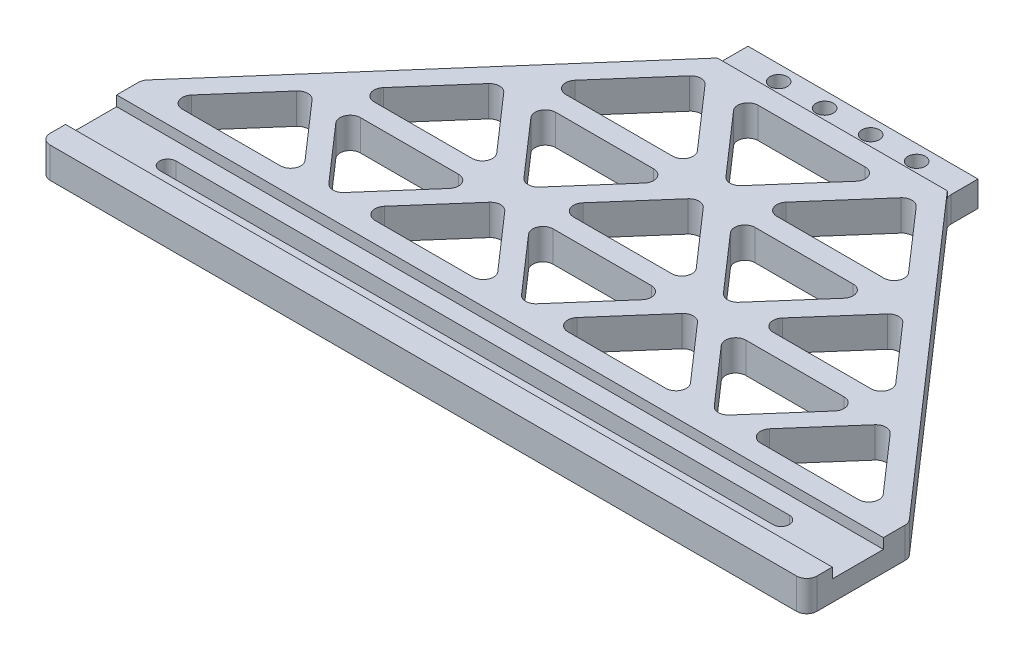
SolidWorks part; units mm, degrees
material "Сплав 2024"
ref_plane "Спереди" through (0, 0, 0) normal (0, 0, 1) x (1, 0, 0)
ref_plane "Сверху" through (0, 0, 0) normal (0, 1, 0) x (1, 0, 0)
ref_plane "Справа" through (0, 0, 0) normal (1, 0, 0) x (0, 0, -1)
sketch "Эскиз1" plane through (0, 0, 0) normal (0, 1, 0) x (1, 0, 0)
  line L0 (-22.5, 0) -> (22.5, 0) construction
  line L1 (-22.5, 3) -> (22.5, 3)
  line L2 (-22.5, 3) -> (-22.5, -3)
  line L3 (-22.5, -3) -> (22.5, -3) construction
  line L4 (22.5, 3) -> (22.5, -3)
  line L5 (-22.5, 3) -> (22.5, -3) construction
  line L6 (-22.5, -3) -> (22.5, 3) construction
  line L7 (0, 3) -> (0, -3) construction
  line L8 (-22.5, -3) -> (-75, -63)
  line L9 (-75, -63) -> (-75, -83)
  line L10 (-75, -83) -> (75, -83)
  line L11 (75, -83) -> (75, -63)
  line L12 (75, -63) -> (22.5, -3)
  line L13 (0, -3) -> (0, -163) construction
  line L14 (75, -63) -> (-75, -63) construction
  line L15 (-13.5, 3) -> (-13.5, -3) construction
  line L16 (-4.5, 3) -> (-4.5, -3) construction
  line L17 (4.5, 3) -> (4.5, -3) construction
  line L18 (13.5, 3) -> (13.5, -3) construction
  point P0 (0, 0)
  point P10 (0, -83)
  dimension "D1" = 45
  dimension "D2" = 6
  dimension "D3" = 150
  dimension "D4" = 80
  dimension "D5" = 20
  dimension "D6" = 9
  dimension "D7" = 9
  dimension "D8" = 9
  dimension "D9" = 9
extrude "Бобышка-Вытянуть1" add sketch "Эскиз1" along normal blind 6
sketch "Эскиз2" plane through (0, 6, 0) normal (0, 1, 0) x (1, 0, 0)
  line L0 (75, -83) -> (75, -63) construction
  line L1 (-75, -78) -> (75, -78)
  line L2 (-75, -78) -> (-75, -68)
  line L3 (-75, -68) -> (75, -68)
  line L4 (75, -78) -> (75, -68)
  line L5 (-75, -83) -> (75, -83) construction
  dimension "D1" = 10
  dimension "D2" = 5
extrude "Вырез-Вытянуть1" cut sketch "Эскиз2" against normal blind 2
sketch "Эскиз3" plane through (0, 6, 0) normal (0, 1, 0) x (1, 0, 0)
  line L1 (-22.5, 3) -> (22.5, 3)
  line L2 (-22.5, 3) -> (-22.5, -3)
  line L3 (-22.5, -3) -> (22.5, -3)
  line L4 (22.5, 3) -> (22.5, -3)
extrude "Вырез-Вытянуть2" cut sketch "Эскиз3" against normal blind 1
hole_wizard "Отверстие с зазором M31" positions "Эскиз8" profile "Эскиз7" hole size "M3" standard "Ansi Metric" end condition through all
sketch "Эскиз8" plane through (0, 0, 0) normal (0, -1, 0) x (-1, 0, 0)
  line L0 (-13.5, 3) -> (-13.5, -3) construction
  line L1 (-4.5, 3) -> (-4.5, -3) construction
  line L2 (4.5, 3) -> (4.5, -3) construction
  line L3 (13.5, 3) -> (13.5, -3) construction
  point P0 (-13.5, 0)
  point P4 (-4.5, 0)
  point P8 (4.5, 0)
  point P12 (13.5, 0)
sketch "Эскиз7" plane through (13.5, 0, 0) normal (1, 0, 0) x (0, 0, -1)
  line L0 (0, 0) -> (0, 6)
  line L1 (0, 6) -> (1.7, 6)
  line L2 (1.7, 6) -> (1.7, 0)
  line L5 (1.7, 0) -> (0, 0)
  line L11 (0, -6.35) -> (0, 107.95) construction
  dimension "Диаметр сквозного отверстия" = 3.4
  dimension "Глубина сквозного отверстия" = 6
sketch "Эскиз9" plane through (0, 4, 0) normal (0, 1, 0) x (1, 0, 0)
  line L0 (-60, -73) -> (60, -73) construction
  line L1 (-60, -71.4) -> (60, -71.4)
  line L2 (-60, -74.6) -> (60, -74.6)
  line L3 (0, -68) -> (0, -78) construction
  line L4 (75, -68) -> (-75, -68) construction
  line L5 (-75, -78) -> (75, -78) construction
  arc A0 (-60, -71.4) -> (-60, -74.6) centre (-60, -73) ccw
  arc A1 (60, -74.6) -> (60, -71.4) centre (60, -73) ccw
  point P2 (0, -73)
  dimension "D1" = 1.6
  dimension "D2" = 120
extrude "Вырез-Вытянуть3" cut sketch "Эскиз9" against normal through all
sketch "Эскиз10" plane through (0, 6, 0) normal (0, 1, 0) x (1, 0, 0)
  line L0 (-2.3315, 13.9753) -> (-85.5296, -81.1082) construction
  line L1 (-1.4219, 18.2649) -> (84.9093, -80.3992) construction
  line L2 (-75, -64) -> (75, -64) construction
  line L3 (-22.5, -3) -> (-75, -63) construction
  line L4 (75, -63) -> (22.5, -3) construction
  line L5 (75, -68) -> (-75, -68) construction
  line L6 (-36.0661, -7) -> (36.2465, -7) construction
  line L7 (-22.5, -3) -> (22.5, -3) construction
  line L8 (-66.3605, -48) -> (66.7235, -48) construction
  line L9 (-59.8686, -44) -> (61.8546, -44) construction
  line L10 (-43.099, -28) -> (53.3779, -28) construction
  line L11 (36.2465, -24) -> (-41.2957, -24) construction
  line L12 (-70.5599, -64) -> (-56.5599, -48)
  line L13 (-56.5599, -48) -> (-42.5599, -64)
  line L14 (-42.5599, -64) -> (-70.5599, -64)
  line L15 (-51.7099, -48) -> (-37.7099, -64)
  line L16 (-37.7099, -64) -> (-23.7099, -48)
  line L17 (-23.7099, -48) -> (-51.7099, -48)
  line L18 (-18.8599, -48) -> (-32.8599, -64)
  line L19 (-32.8599, -64) -> (-4.8599, -64)
  line L20 (-4.8599, -64) -> (-18.8599, -48)
  line L21 (-14.0099, -48) -> (-0.0099, -64)
  line L22 (-0.0099, -64) -> (13.9901, -48)
  line L23 (13.9901, -48) -> (-14.0099, -48)
  line L24 (18.8401, -48) -> (4.8401, -64)
  line L25 (4.8401, -64) -> (32.8401, -64)
  line L26 (32.8401, -64) -> (18.8401, -48)
  line L27 (23.6901, -48) -> (37.6901, -64)
  line L28 (37.6901, -64) -> (51.6901, -48)
  line L29 (51.6901, -48) -> (23.6901, -48)
  line L31 (42.5401, -64) -> (70.5401, -64)
  line L32 (70.5401, -64) -> (56.5401, -48)
  line L33 (56.5401, -48) -> (42.5401, -64)
  line L34 (-75, -63) -> (-75, -68) construction
  line L35 (75, -68) -> (75, -63) construction
  line L36 (-53.0599, -44) -> (-39.0599, -28)
  line L37 (-39.0599, -28) -> (-25.0599, -44)
  line L38 (-25.0599, -44) -> (-53.0599, -44)
  line L39 (-33.5455, -28) -> (-19.5455, -44)
  line L40 (-19.5455, -44) -> (-5.5455, -28)
  line L41 (-5.5455, -28) -> (-33.5455, -28)
  line L42 (-0.0312, -28) -> (-14.0312, -44)
  line L43 (-14.0312, -44) -> (13.9688, -44)
  line L44 (13.9688, -44) -> (-0.0312, -28)
  line L45 (5.4832, -28) -> (19.4832, -44)
  line L46 (19.4832, -44) -> (33.4832, -28)
  line L47 (33.4832, -28) -> (5.4832, -28)
  line L48 (24.9976, -44) -> (38.9976, -28)
  line L49 (38.9976, -28) -> (52.9976, -44)
  line L50 (52.9976, -44) -> (24.9976, -44)
  line L51 (-35.5599, -24) -> (-20.6849, -7)
  line L52 (-20.6849, -7) -> (-5.8099, -24)
  line L53 (-5.8099, -24) -> (-35.5599, -24)
  line L54 (-14.9048, -7) -> (-0.0298, -24)
  line L55 (-0.0298, -24) -> (14.8452, -7)
  line L56 (14.8452, -7) -> (-14.9048, -7)
  line L57 (20.6254, -7) -> (5.7504, -24)
  line L58 (5.7504, -24) -> (35.5004, -24)
  line L59 (35.5004, -24) -> (20.6254, -7)
  dimension "D1" = 4
  dimension "D2" = 4
  dimension "D3" = 4
  dimension "D4" = 4
  dimension "D5" = 4
  dimension "D6" = 4
  dimension "D7" = 48.814
  dimension "D8" = 48.814
  dimension "D9" = 57
  dimension "D10" = 16
  dimension "D11" = 16
  dimension "D12" = 82.372
  dimension "D13" = 82.372
  dimension "D14" = 82.372
  dimension "D15" = 82.372
  dimension "D16" = 3.65
  dimension "D17" = 3.65
  dimension "D18" = 82.372
  dimension "D19" = 82.372
  dimension "D20" = 3.65
  dimension "D21" = 3.65
  dimension "D22" = 3.65
  dimension "D23" = 3.65
  dimension "D24" = 82.372
  dimension "D25" = 4.15
  dimension "D26" = 4.15
  dimension "D27" = 4.15
  dimension "D28" = 82.372
  dimension "D29" = 82.372
  dimension "D30" = 82.372
  dimension "D31" = 82.372
  dimension "D32" = 4.15
  dimension "D33" = 82.372
  dimension "D34" = 82.372
  dimension "D35" = 82.372
  dimension "D36" = 82.372
  dimension "D37" = 4.35
  dimension "D38" = 4.35
extrude "Вырез-Вытянуть4" cut sketch "Эскиз10" against normal up to next
fillet "Скругление1" radius 2 51 edges at (18.8401, 3, 48) (23.6901, 3, 48) (-14.0099, 3, 48) (-51.7099, 3, 48) (-33.5455, 3, 28) (5.4832, 3, 28) (5.7504, 3, 24) (24.9976, 3, 44) (4.8401, 3, 64) (-32.8599, 3, 64) (-70.5599, 3, 64) (-14.0312, 3, 44) (-53.0599, 3, 44) (-35.5599, 3, 24) (-42.5599, 3, 64) (-25.0599, 3, 44) (-4.8599, 3, 64) (35.5004, 3, 24) (52.9976, 3, 44) (70.5401, 3, 64) (32.8401, 3, 64) (13.9688, 3, 44) (-5.8099, 3, 24) (-0.0298, 3, 24) (-37.7099, 3, 64) (-0.0099, 3, 64) (19.4832, 3, 44) (37.6901, 3, 64) (56.5401, 3, 48) (38.9976, 3, 28) (-0.0312, 3, 28) (-18.8599, 3, 48) (-56.5599, 3, 48) (-39.0599, 3, 28) (-20.6849, 3, 7) (20.6254, 3, 7) (-23.7099, 3, 48) (13.9901, 3, 48) (-5.5455, 3, 28) (51.6901, 3, 48) (33.4832, 3, 28) (14.8452, 3, 7) (-75, 3, 63) (-75, 3, 83) (75, 3, 83) (75, 3, 63) (22.5, 2.5, 3) (-22.5, 2.5, 3) (-19.5455, 3, 44) (42.5401, 3, 64) (-14.9048, 3, 7)
fillet "Скругление2" [suppressed] radius 2
equation "\"D6@Эскиз1\"=\"D1@Эскиз1\"/5"
equation "\"D7@Эскиз1\"=\"D6@Эскиз1\""
equation "\"D8@Эскиз1\"=\"D6@Эскиз1\""
equation "\"D9@Эскиз1\"=\"D6@Эскиз1\""
equation "\"D13@Эскиз10\"=\"D12@Эскиз10\""
equation "\"D14@Эскиз10\"=\"D12@Эскиз10\""
equation "\"D15@Эскиз10\"=\"D12@Эскиз10\""
equation "\"D18@Эскиз10\"=\"D12@Эскиз10\""
equation "\"D19@Эскиз10\"=\"D12@Эскиз10\""
equation "\"D24@Эскиз10\"=\"D12@Эскиз10\""
equation "\"D17@Эскиз10\"=\"D16@Эскиз10\""
equation "\"D23@Эскиз10\"=\"D16@Эскиз10\""
equation "\"D22@Эскиз10\"=\"D16@Эскиз10\""
equation "\"D20@Эскиз10\"=\"D16@Эскиз10\""
equation "\"D21@Эскиз10\"=\"D16@Эскиз10\""
equation "\"D28@Эскиз10\"=\"D12@Эскиз10\""
equation "\"D29@Эскиз10\"=\"D28@Эскиз10\""
equation "\"D30@Эскиз10\"=\"D28@Эскиз10\""
equation "\"D31@Эскиз10\"=\"D28@Эскиз10\""
equation "\"D32@Эскиз10\"=\"D25@Эскиз10\""
equation "\"D26@Эскиз10\"=\"D25@Эскиз10\""
equation "\"D27@Эскиз10\"=\"D25@Эскиз10\""
equation "\"D33@Эскиз10\"=\"D28@Эскиз10\""
equation "\"D34@Эскиз10\"=\"D12@Эскиз10\""
equation "\"D35@Эскиз10\"=\"D34@Эскиз10\""
equation "\"D36@Эскиз10\"=\"D34@Эскиз10\""
equation "\"D38@Эскиз10\"=\"D37@Эскиз10\""
